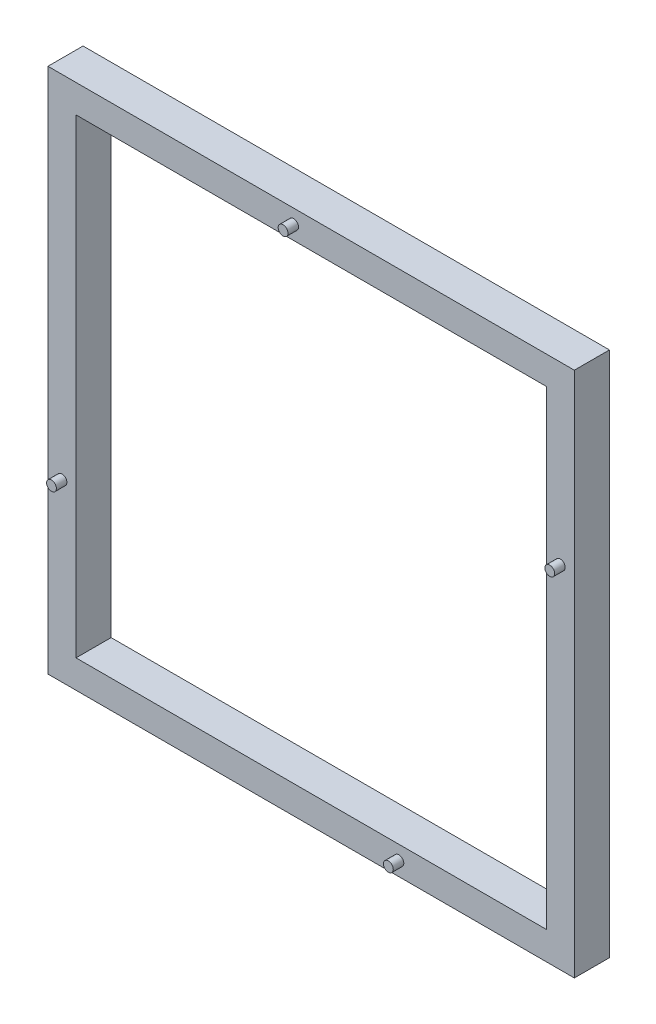
SolidWorks part; units mm, degrees
ref_plane "Front Plane" through (0, 0, 0) normal (0, 0, 1) x (1, 0, 0)
ref_plane "Top Plane" through (0, 0, 0) normal (0, 1, 0) x (1, 0, 0)
ref_plane "Right Plane" through (0, 0, 0) normal (1, 0, 0) x (0, 0, -1)
sketch "Sketch1" plane through (0, 0, 0) normal (0, 0, 1) x (1, 0, 0)
  line L1 (-72.2107, 36.2603) -> (77.7893, 36.2603)
  line L2 (-72.2107, 36.2603) -> (-72.2107, -113.7397)
  line L3 (-72.2107, -113.7397) -> (77.7893, -113.7397)
  line L4 (77.7893, 36.2603) -> (77.7893, -113.7397)
  dimension "D1" = 150
  dimension "D2" = 150
extrude "Boss-Extrude1" add sketch "Sketch1" along normal blind 10
sketch "Sketch2" plane through (0, 0, 10) normal (0, 0, 1) x (1, 0, 0)
  line L0 (77.7893, 36.2603) -> (-72.2107, 36.2603) construction
  line L1 (69.7893, 28.2603) -> (-64.2107, 28.2603)
  line L2 (69.7893, 28.2603) -> (69.7893, -105.7397)
  line L3 (69.7893, -105.7397) -> (-64.2107, -105.7397)
  line L4 (-64.2107, 28.2603) -> (-64.2107, -105.7397)
  line L5 (77.7893, -113.7397) -> (77.7893, 36.2603) construction
  line L6 (-72.2107, -113.7397) -> (77.7893, -113.7397) construction
  line L7 (-72.2107, 36.2603) -> (-72.2107, -113.7397) construction
  dimension "D1" = 8
  dimension "D2" = 8
  dimension "D3" = 8
  dimension "D4" = 8
extrude "Cut-Extrude1" cut sketch "Sketch2" against normal through all
sketch "Sketch3" plane through (0, 0, 10) normal (0, 0, 1) x (1, 0, 0)
  line L0 (-72.2107, 36.2603) -> (-72.2107, -113.7397) construction
  line L1 (-72.2107, -113.7397) -> (77.7893, -113.7397) construction
  line L2 (77.7893, -113.7397) -> (77.7893, 36.2603) construction
  line L3 (77.7893, 36.2603) -> (-72.2107, 36.2603) construction
  circle A0 centre (73.7893, -13.7397) radius 1.4
  circle A1 centre (27.7893, -109.7397) radius 1.4
  circle A2 centre (-68.2107, -63.7397) radius 1.4
  circle A3 centre (-2.2107, 32.2603) radius 1.4
  point P0 (-2.2107, 32.2603)
  point P1 (73.7893, -13.7397)
  point P2 (27.7893, -109.7397)
  point P3 (-68.2107, -63.7397)
  dimension "D9" = 2.8
  dimension "D10" = 2.8
  dimension "D11" = 2.8
  dimension "D12" = 2.8
  dimension "D1" = 4
  dimension "D2" = 50
  dimension "D3" = 4
  dimension "D4" = 50
  dimension "D5" = 4
  dimension "D6" = 50
  dimension "D7" = 4
  dimension "D8" = 70
extrude "Boss-Extrude2" add sketch "Sketch3" along normal blind 3
